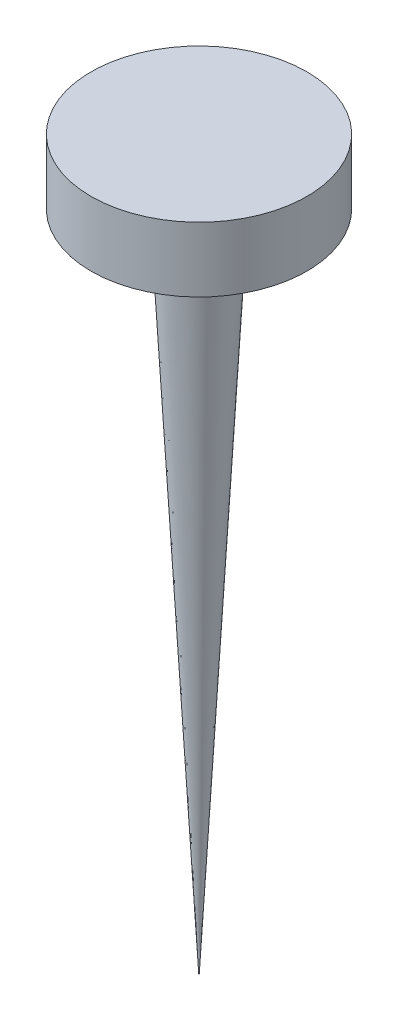
SolidWorks part; units mm, degrees
ref_plane "Front Plane" through (0, 0, 0) normal (0, 0, 1) x (1, 0, 0)
ref_plane "Top Plane" through (0, 0, 0) normal (0, 1, 0) x (1, 0, 0)
ref_plane "Right Plane" through (0, 0, 0) normal (1, 0, 0) x (0, 0, -1)
sketch "Sketch1" plane through (0, 0, 0) normal (0, 0, 1) x (1, 0, 0)
  line L1 (-0.5, -0.3) -> (-0.5, 0)
  line L2 (-0.5, -0.3) -> (-0.1617, -0.3)
  line L5 (-0.5, -0.3) -> (0, -0.15) construction
  line L6 (-0.5, 0) -> (0, -0.15) construction
  line L7 (-0.1617, -0.3) -> (0, -3.385)
  line L10 (0, 0) -> (0, -3.385)
  line L11 (-0.5, 0) -> (0, 0)
  point P1 (0, -0.15)
  dimension "D1" = 0.3
  dimension "D2" = 0.5
  dimension "D3" = 3
  dimension "D4" = 3.385
revolve "Revolve2" add sketch "Sketch1" angle 360 about L10
